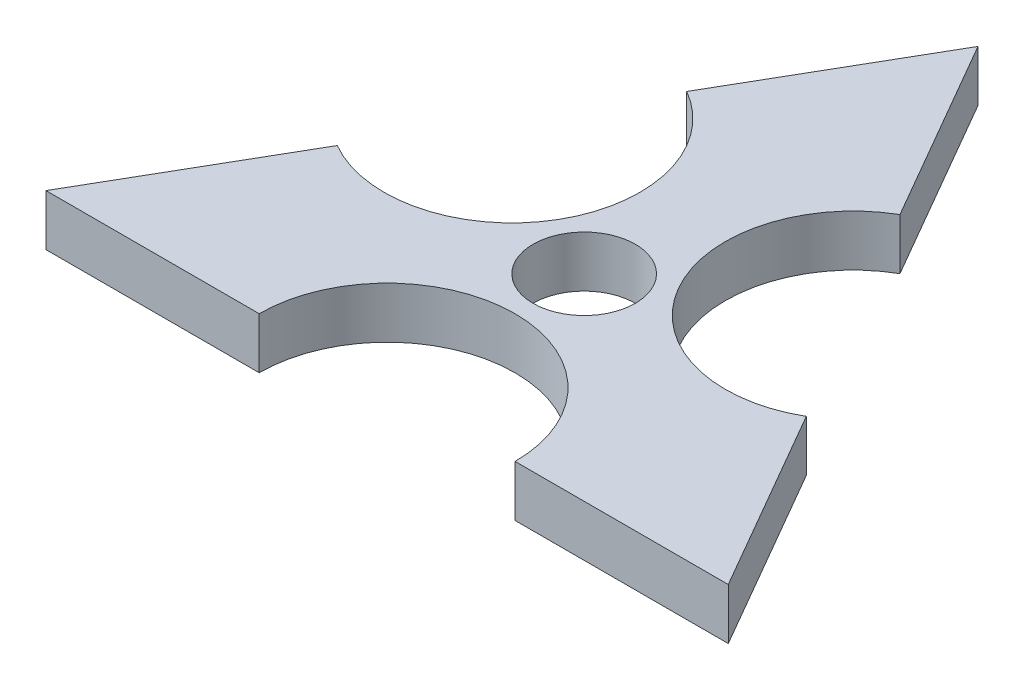
SolidWorks part; units mm, degrees
ref_plane "Front Plane" through (0, 0, 0) normal (0, 0, 1) x (1, 0, 0)
ref_plane "Top Plane" through (0, 0, 0) normal (0, 1, 0) x (1, 0, 0)
ref_plane "Right Plane" through (0, 0, 0) normal (1, 0, 0) x (0, 0, -1)
sketch "Sketch1" plane through (0, 0, 0) normal (0, 1, 0) x (1, 0, 0)
  line L2 (0.3051, 0) -> (0.3051, -73.6281) construction
  line L3 (0.3051, 34.641) -> (-19.6949, 0)
  line L4 (-19.6949, 0) -> (20.3051, 0)
  line L5 (20.3051, 0) -> (0.3051, 34.641)
  line L7 (0.3051, 34.641) -> (0.3051, 0) construction
  line L10 (20.3051, 0) -> (-9.6949, 17.3205) construction
  line L11 (-19.6949, 0) -> (10.3051, 17.3205) construction
  circle A0 centre (10.3051, 17.3205) radius 7.5
  circle A1 centre (-9.6949, 17.3205) radius 7.5
  circle A2 centre (0.3051, 0) radius 7.5
  circle A3 centre (0.3051, 11.552) radius 3
  point P21 (20.3051, 0)
  dimension "D3" = 15
  dimension "D4" = 40
extrude "Boss-Extrude1" add sketch "Sketch1" along normal blind 3 contours A2 L4 L5 A0 L3 A1
